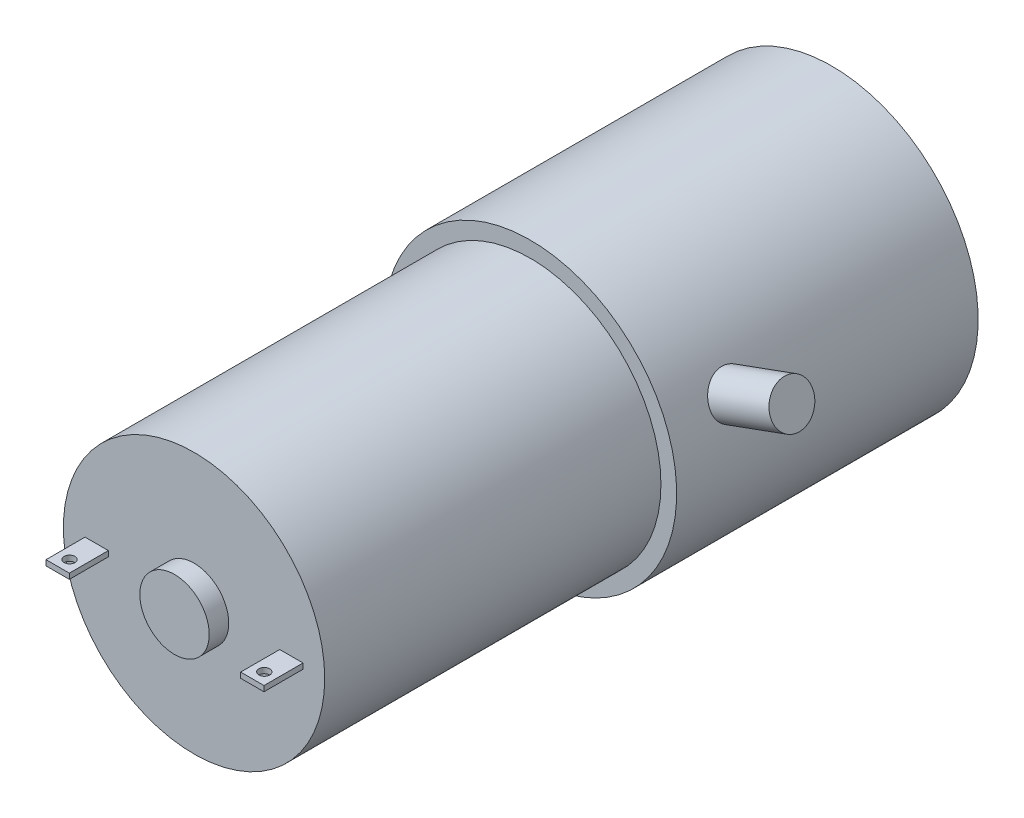
SolidWorks part; units mm, degrees
ref_plane "Plan de face" through (0, 0, 0) normal (0, 0, 1) x (1, 0, 0)
ref_plane "Plan de dessus" through (0, 0, 0) normal (0, 1, 0) x (1, 0, 0)
ref_plane "Plan de droite" through (0, 0, 0) normal (1, 0, 0) x (0, 0, -1)
sketch "Esquisse1" plane through (0, 0, 0) normal (0, 0, 1) x (1, 0, 0)
  circle A0 centre (0, 0) radius 12.05
  dimension "D1" = 24.1
extrude "Boss.-Extru.1" add sketch "Esquisse1" along normal blind 31
sketch "Esquisse3" plane through (0, 0, 0) normal (0, 0, -1) x (-1, 0, 0)
  circle A0 centre (0, 0) radius 13.5
  dimension "D1" = 27
extrude "Boss.-Extru.2" add sketch "Esquisse3" along normal blind 27.8
sketch "Esquisse8" plane through (0, 0, 31) normal (0, 0, 1) x (1, 0, 0)
  circle A0 centre (0, 0) radius 3.2
  dimension "D1" = 6.4
extrude "Boss.-Extru.6" add sketch "Esquisse8" along normal blind 1.8
sketch "Esquisse4" plane through (0, 0, -27.8) normal (0, 0, -1) x (-1, 0, 0)
  circle A0 centre (0, 0) radius 2.2
  dimension "D1" = 4.4
extrude "Boss.-Extru.3" add sketch "Esquisse4" along normal blind 6
ref_plane "Plan1" through (12.6859, 4.6173, 0) normal (0.9397, 0.342, 0) x (0, 0, 1)
sketch "Esquisse5" plane through (12.6859, 4.6173, 0) normal (0.9397, 0.342, 0) x (0, 0, 1)
  line L0 (0, 0) -> (-27.8, 0) construction
  line L1 (-27.8, 13.5) -> (-27.8, -13.5) construction
  circle A0 centre (-5.8, 0) radius 2
  dimension "D1" = 4
  dimension "D2" = 22
extrude "Boss.-Extru.4" add sketch "Esquisse5" against normal up to next from offset 6 separate body
sketch "Esquisse7" plane through (0, 0, 0) normal (0, 1, 0) x (1, 0, 0)
  line L0 (-10.05, -31) -> (-7.9, -31)
  line L1 (-12.05, -31) -> (12.05, -31) construction
  line L2 (-7.9, -31) -> (-7.9, -34.6)
  line L3 (-7.9, -34.6) -> (-10.05, -34.6)
  line L4 (-10.05, -34.6) -> (-10.05, -31)
  line L5 (0, -31) -> (0, -33.1114) construction
  line L6 (10.05, -34.6) -> (10.05, -31)
  line L7 (7.9, -34.6) -> (10.05, -34.6)
  line L8 (7.9, -31) -> (7.9, -34.6)
  line L9 (10.05, -31) -> (7.9, -31)
  line L10 (-8.975, -34.6) -> (-8.975, -31) construction
  circle A0 centre (-8.975, -33.5) radius 0.5
  circle A1 centre (8.975, -33.5) radius 0.5
  dimension "D3" = 1
  dimension "D1" = 2.15
  dimension "D2" = 3.6
  dimension "D4" = 1.1
  dimension "D5" = 15.8
extrude "Boss.-Extru.5" add sketch "Esquisse7" along normal mid plane 0.5
